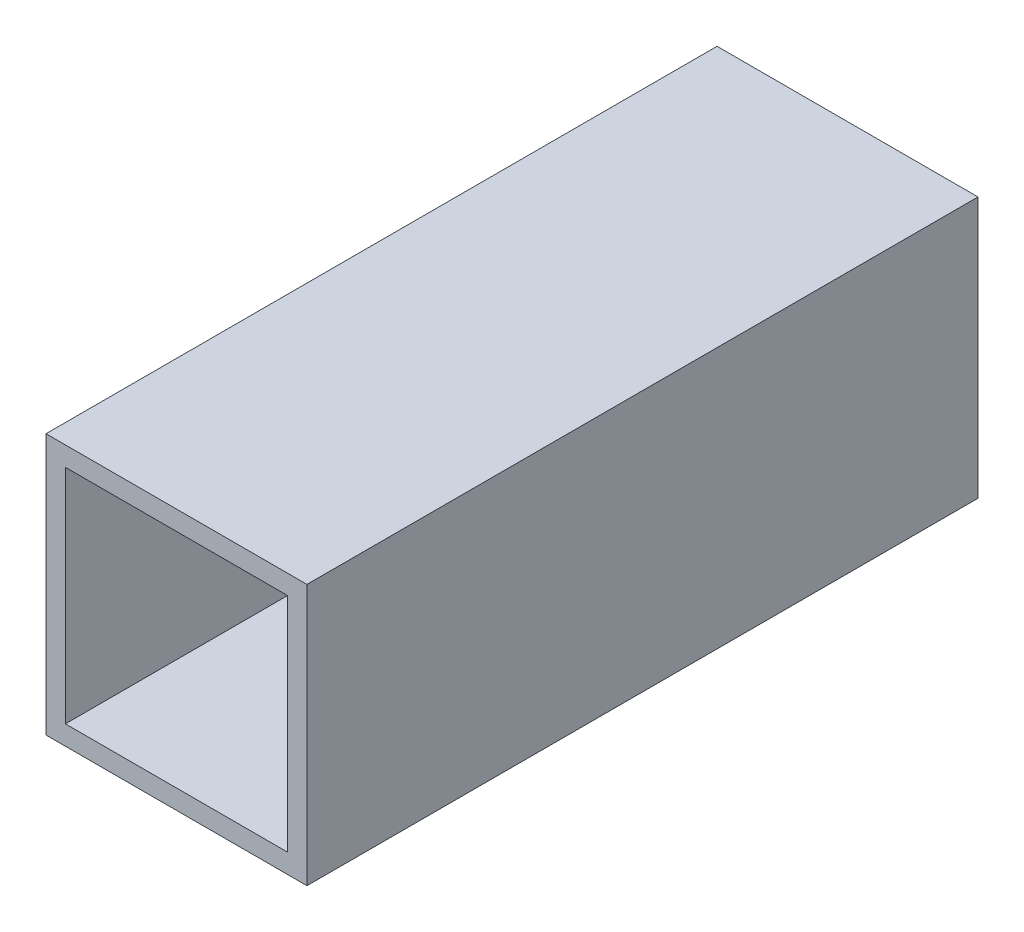
SolidWorks part; units mm, degrees
material "6061 Alloy"
ref_plane "Front Plane" through (0, 0, 0) normal (0, 0, 1) x (1, 0, 0)
ref_plane "Top Plane" through (0, 0, 0) normal (0, 1, 0) x (1, 0, 0)
ref_plane "Right Plane" through (0, 0, 0) normal (1, 0, 0) x (0, 0, -1)
sketch "Sketch1" plane through (0, 0, 0) normal (0, 0, 1) x (1, 0, 0)
  line L1 (-22.225, 22.225) -> (22.225, 22.225)
  line L2 (-22.225, 22.225) -> (-22.225, -22.225)
  line L3 (-22.225, -22.225) -> (22.225, -22.225)
  line L4 (22.225, 22.225) -> (22.225, -22.225)
  line L5 (-22.225, 22.225) -> (22.225, -22.225) construction
  line L6 (-22.225, -22.225) -> (22.225, 22.225) construction
  line L7 (-18.923, 18.923) -> (18.923, 18.923)
  line L8 (-18.923, 18.923) -> (-18.923, -18.923)
  line L9 (-18.923, -18.923) -> (18.923, -18.923)
  line L10 (18.923, 18.923) -> (18.923, -18.923)
  line L11 (-18.923, 18.923) -> (18.923, -18.923) construction
  line L12 (-18.923, -18.923) -> (18.923, 18.923) construction
  point P0 (0, 0)
  point P6 (0, 0)
  dimension "D1" = 44.45
  dimension "D2" = 44.45
  dimension "D3" = 3.302
extrude "Boss-Extrude1" add sketch "Sketch1" along normal blind 114.3
